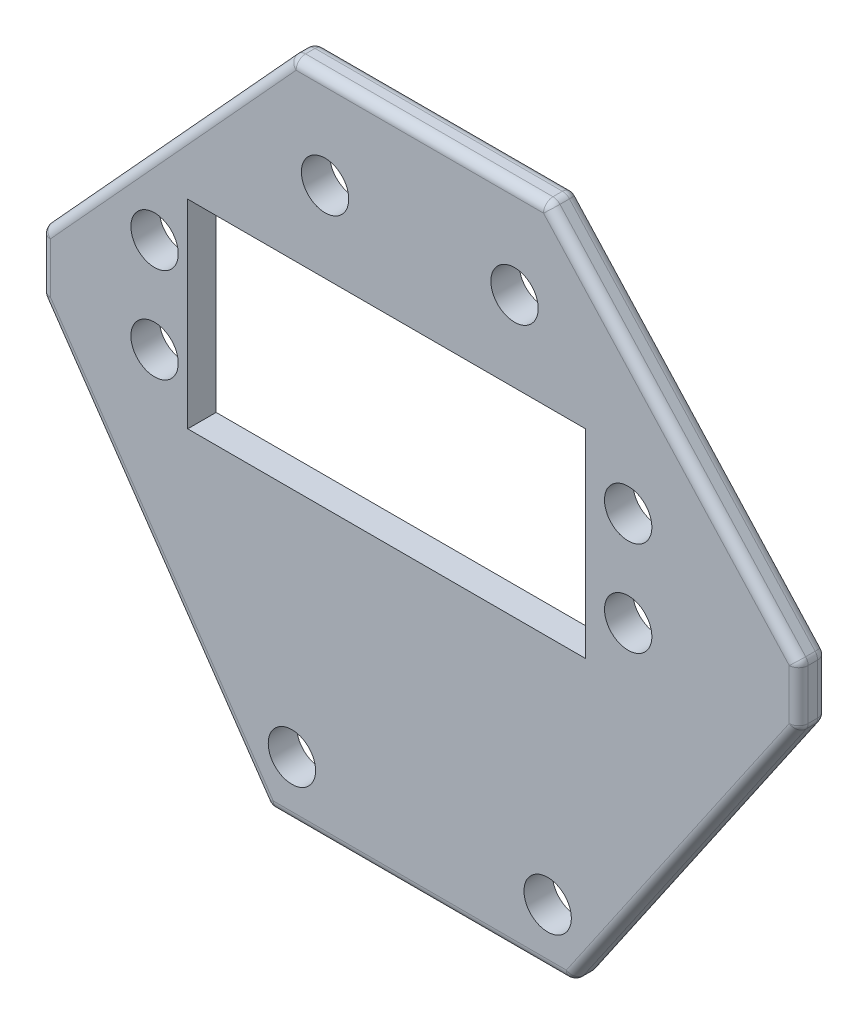
SolidWorks part; units mm, degrees
ref_plane "Front Plane" through (0, 0, 0) normal (0, 0, 1) x (1, 0, 0)
ref_plane "Top Plane" through (0, 0, 0) normal (0, 1, 0) x (1, 0, 0)
ref_plane "Right Plane" through (0, 0, 0) normal (1, 0, 0) x (0, 0, -1)
sketch "Sketch1" plane through (0, 0, 0) normal (0, 0, 1) x (1, 0, 0)
  line L0 (-13.5, 29) -> (-40, 0)
  line L1 (-40, 0) -> (-40, -6)
  line L2 (-40, -6) -> (-16, -41)
  line L3 (-16, -41) -> (16, -41)
  line L4 (16, -41) -> (40, -6)
  line L5 (40, -6) -> (40, 0)
  line L6 (40, 0) -> (13.5, 29)
  line L7 (13.5, 29) -> (-13.5, 29)
extrude "Boss-Extrude1" add sketch "Sketch1" along normal blind 3
sketch "Sketch2" plane through (0, 0, 0) normal (0, 0, -1) x (-1, 0, 0)
  circle A0 centre (-10, 19) radius 2.5
  circle A1 centre (10, 19) radius 2.5
  circle A2 centre (-13.5, -35) radius 2.5
  circle A3 centre (13.5, -35) radius 2.5
extrude "Cut-Extrude1" cut sketch "Sketch2" against normal blind 10
sketch "Sketch3" plane through (0, 0, 0) normal (0, 0, -1) x (-1, 0, 0)
  line L0 (13.5, 0) -> (24.5, 0) construction
  line L2 (24.5, 0) -> (24.5, 10.5)
  line L3 (24.5, 10.5) -> (-17.5, 10.5)
  line L4 (-17.5, 10.5) -> (-17.5, -10.5)
  line L5 (-17.5, -10.5) -> (24.5, -10.5)
  line L6 (24.5, -10.5) -> (24.5, 0)
  dimension "D1" = 11
  dimension "D2" = 21
  dimension "D3" = 42
extrude "Cut-Extrude2" cut sketch "Sketch3" against normal blind 10
sketch "Sketch5" plane through (0, 0, 3) normal (0, 0, 1) x (1, 0, 0)
  line L0 (-24.5, 0) -> (-38.0829, 0) construction
  line L1 (-24.5, 10.5) -> (-24.5, -10.5) construction
  line L2 (17.5, 0) -> (34.2999, 0) construction
  line L3 (17.5, -10.5) -> (17.5, 10.5) construction
  circle A0 centre (-28, -5) radius 2.5
  circle A1 centre (-28, 5) radius 2.5
  circle A2 centre (22, -5) radius 2.5
  circle A3 centre (22, 5) radius 2.5
  dimension "D1" = 5
  dimension "D2" = 5
  dimension "D3" = 3.5
  dimension "D4" = 5
  dimension "D5" = 4.5
  dimension "D6" = 5
extrude "Cut-Extrude3" cut sketch "Sketch5" against normal blind 10
fillet "Fillet1" radius 1 24 edges at (-28, -23.5, 3) (-28, -23.5, 0) (-16, -41, 1.5) (0, -41, 3) (0, -41, 0) (16, -41, 1.5) (28, -23.5, 3) (28, -23.5, 0) (40, -6, 1.5) (40, -3, 3) (40, -3, 0) (40, 0, 1.5) (26.75, 14.5, 3) (13.5, 29, 1.5) (26.75, 14.5, 0) (-40, -3, 3) (-40, -6, 1.5) (-40, -3, 0) (-13.5, 29, 1.5) (-26.75, 14.5, 3) (-40, 0, 1.5) (-26.75, 14.5, 0) (0, 29, 3) (0, 29, 0)
